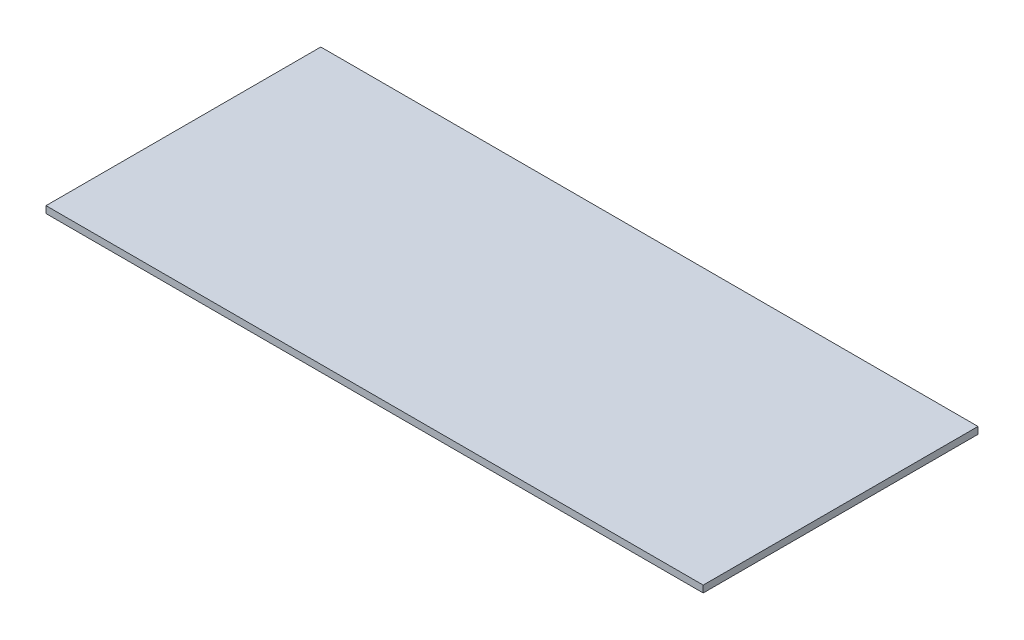
SolidWorks part; units mm, degrees
material "Acrílico (Impacto medio-alto)"
ref_plane "Alzado" through (0, 0, 0) normal (0, 0, 1) x (1, 0, 0)
ref_plane "Planta" through (0, 0, 0) normal (0, 1, 0) x (1, 0, 0)
ref_plane "Vista lateral" through (0, 0, 0) normal (1, 0, 0) x (0, 0, -1)
sketch "Sketch1" plane through (0, 0, 0) normal (0, 1, 0) x (1, 0, 0)
  line L1 (-143.5, -60) -> (143.5, -60)
  line L2 (-143.5, -60) -> (-143.5, 60)
  line L3 (-143.5, 60) -> (143.5, 60)
  line L4 (143.5, -60) -> (143.5, 60)
  line L5 (-143.5, -60) -> (143.5, 60) construction
  line L6 (-143.5, 60) -> (143.5, -60) construction
  line L7 (-53.5, -123) -> (53.5, -123) construction
  line L9 (-143.5, -60) -> (-143.5, -123) construction
  line L10 (-143.5, -123) -> (-53.5, -123) construction
  line L11 (143.5, -60) -> (143.5, -123) construction
  line L12 (143.5, -123) -> (53.5, -123) construction
  point P0 (0, 0)
  point P6 (0, -123)
  point P9 (0, -60)
  dimension "D1" = 120
  dimension "D2" = 287
  dimension "D3" = 63
  dimension "D4" = 107
extrude "Boss-Extrude1" add sketch "Sketch1" along normal blind 3
